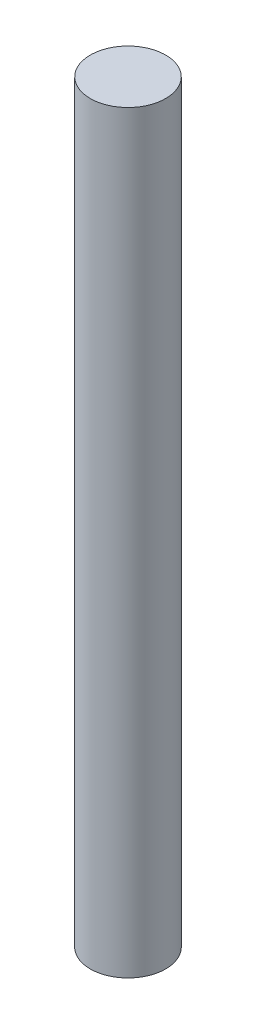
SolidWorks part; units mm, degrees
ref_plane "Front" through (0, 0, 0) normal (0, 0, 1) x (1, 0, 0)
ref_plane "Top" through (0, 0, 0) normal (0, 1, 0) x (1, 0, 0)
ref_plane "Right" through (0, 0, 0) normal (1, 0, 0) x (0, 0, -1)
sketch "Skizze1" plane through (0, 0, 0) normal (0, 1, 0) x (1, 0, 0)
  circle A0 centre (0, 0) radius 15
  dimension "D1" = 30
extrude "Aufsatz-Linear austragen1" add sketch "Skizze1" along normal blind 300
ref_plane "Ebene1" through (0, 262, 0) normal (0, 1, 0) x (1, 0, 0)
